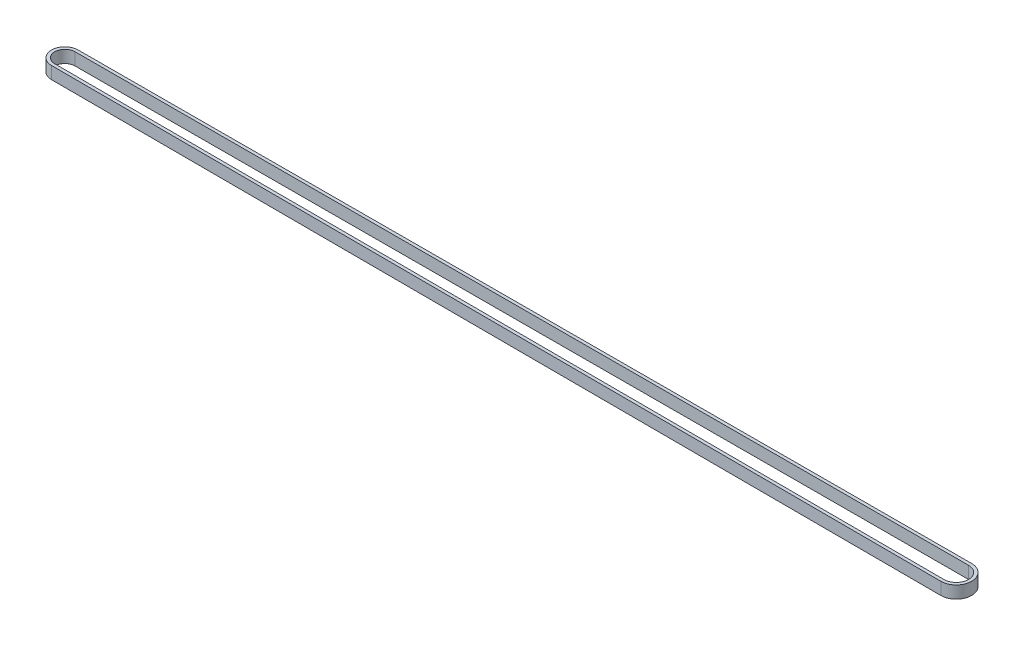
SolidWorks part; units mm, degrees
ref_plane "Alzado" through (0, 0, 0) normal (0, 0, 1) x (1, 0, 0)
ref_plane "Planta" through (0, 0, 0) normal (0, 1, 0) x (1, 0, 0)
ref_plane "Vista lateral" through (0, 0, 0) normal (1, 0, 0) x (0, 0, -1)
sketch "Croquis1" plane through (0, 0, 0) normal (0, 1, 0) x (1, 0, 0)
  line L0 (-60.1415, 5) -> (373.5562, 6)
  line L1 (-60.1415, -5) -> (373.5562, -6)
  line L2 (-60.145, 6.5) -> (373.5527, 7.5)
  line L3 (-60.145, -6.5) -> (373.5527, -7.5)
  line L4 (0, 0) -> (-60.13, 0) construction
  circle A0 centre (-60.13, 0) radius 5 construction
  circle A1 centre (373.57, 0) radius 6 construction
  arc A2 (-60.1415, -5) -> (-60.1415, 5) centre (-60.13, 0) cw
  arc A3 (373.5562, 6) -> (373.5562, -6) centre (373.57, 0) cw
  arc A4 (373.5527, 7.5) -> (373.5527, -7.5) centre (373.57, 0) cw
  arc A5 (-60.145, -6.5) -> (-60.145, 6.5) centre (-60.13, 0) cw
  dimension "D1" = 10
  dimension "D2" = 12
  dimension "D3" = 433.7
  dimension "D5" = 60.13
  dimension "D4" = 1.5
extrude "Saliente-Extruir1" add sketch "Croquis1" along normal blind 6
